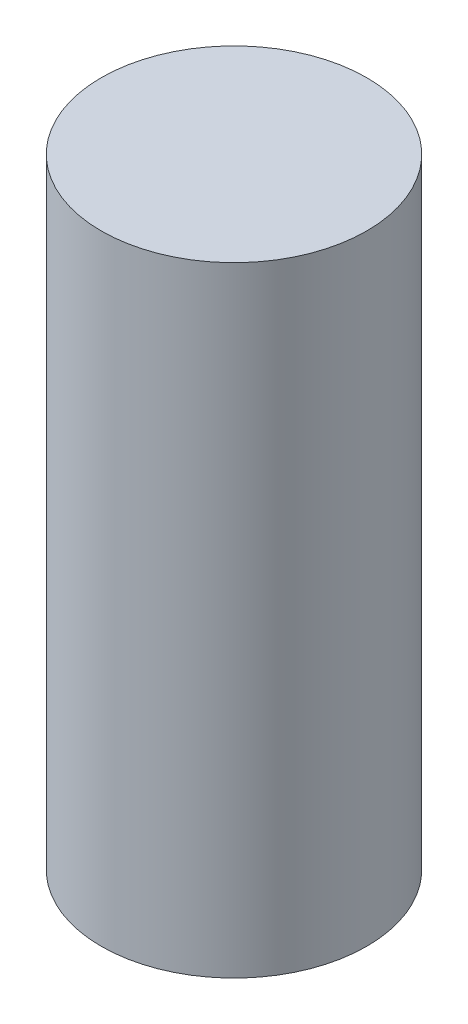
SolidWorks part; units mm, degrees
ref_plane "Front Plane" through (0, 0, 0) normal (0, 0, 1) x (1, 0, 0)
ref_plane "Top Plane" through (0, 0, 0) normal (0, 1, 0) x (1, 0, 0)
ref_plane "Right Plane" through (0, 0, 0) normal (1, 0, 0) x (0, 0, -1)
sketch "Sketch1" plane through (0, 0, 0) normal (0, 1, 0) x (1, 0, 0)
  circle A0 centre (0, 0) radius 3
  dimension "D1" = 6
extrude "Boss-Extrude1" add sketch "Sketch1" along normal blind 14
